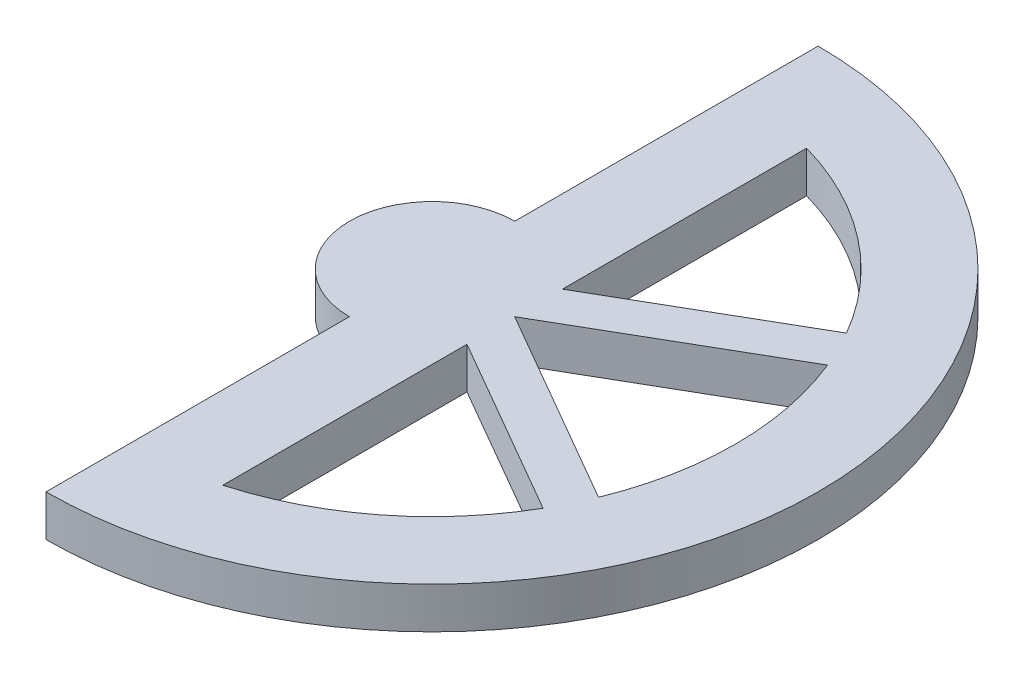
SolidWorks part; units mm, degrees
ref_plane "Front Plane" through (0, 0, 0) normal (0, 0, 1) x (1, 0, 0)
ref_plane "Top Plane" through (0, 0, 0) normal (0, 1, 0) x (1, 0, 0)
ref_plane "Right Plane" through (0, 0, 0) normal (1, 0, 0) x (0, 0, -1)
sketch "Sketch1" plane through (0, 0, 0) normal (0, 1, 0) x (1, 0, 0)
  line L0 (0, 29.6545) -> (0, 6.35)
  line L1 (6.35, 22.4227) -> (6.35, 3.6662)
  line L2 (6.35, 0) -> (21.5816, -8.794)
  line L3 (6.35, -3.6662) -> (20.1823, -11.6522)
  line L4 (6.35, 0) -> (21.5816, 8.794)
  line L5 (6.35, 3.6662) -> (20.1823, 11.6523)
  line L6 (0, -6.35) -> (0, -29.6545)
  line L7 (6.35, -3.6662) -> (6.35, -22.4227)
  arc A0 (0, -29.6545) -> (0, 29.6545) centre (0, 0) ccw
  arc A1 (0, 6.35) -> (0, -6.35) centre (0, 0) ccw
  arc A2 (6.35, -22.4227) -> (20.1823, -11.6522) centre (0, 0) ccw
  arc A3 (21.5816, -8.794) -> (21.5816, 8.794) centre (0, 0) ccw
  arc A4 (20.1823, 11.6523) -> (6.35, 22.4227) centre (0, 0) ccw
  dimension "D1" = 59.309
  dimension "D2" = 12.7
  dimension "D3" = 6.35
  dimension "D4" = 6.35
  dimension "D5" = 3.175
  dimension "D6" = 3.175
  dimension "D7" = 60
  dimension "D8" = 60
extrude "Boss-Extrude1" add sketch "Sketch1" along normal blind 3.175
sketch "Sketch2" plane through (0, 3.175, 0) normal (0, 1, 0) x (1, 0, 0)
  line L0 (2.0092, 29.5864) -> (2.7303, 27.4697)
  line L1 (2.7303, 27.4697) -> (4.712, 27.2)
  line L2 (4.712, 27.2) -> (5.9726, 29.0468)
  line L3 (5.9726, 29.0468) -> (2.0092, 29.5864)
  line L4 (2.0092, 29.5864) -> (1.4886, 25.7623) construction
  line L5 (2.7303, 27.4697) -> (2.2965, 24.2831) construction
  line L6 (4.712, 27.2) -> (4.2511, 23.8143) construction
  line L7 (5.9726, 29.0468) -> (5.4431, 25.157) construction
  line L8 (0, 29.6545) -> (-0.3236, 27.2771) construction
  arc A0 (0, -29.6545) -> (0, 29.6545) centre (0, 0) ccw construction
  dimension "D1" = 2
  dimension "D2" = 1
  dimension "D3" = 1
  dimension "D4" = 2
  dimension "D5" = 2
